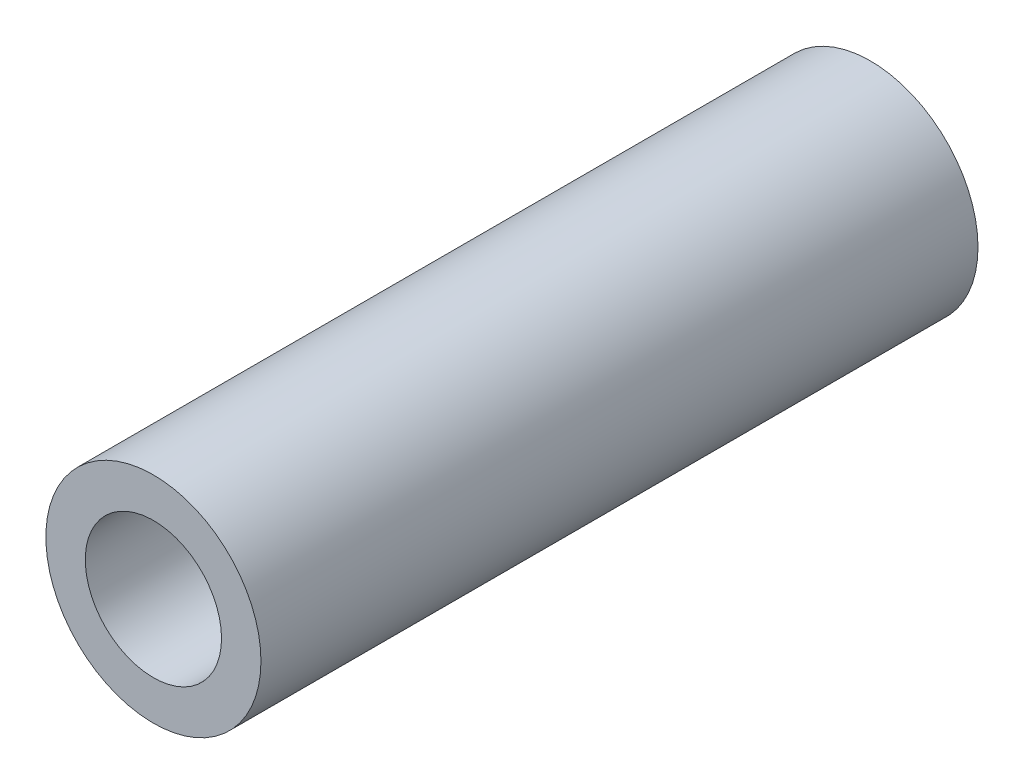
SolidWorks part; units mm, degrees
ref_plane "Front Plane" through (0, 0, 0) normal (0, 0, 1) x (1, 0, 0)
ref_plane "Top Plane" through (0, 0, 0) normal (0, 1, 0) x (1, 0, 0)
ref_plane "Right Plane" through (0, 0, 0) normal (1, 0, 0) x (0, 0, -1)
sketch "Sketch2" plane through (0, 0, 0) normal (0, 0, 1) x (1, 0, 0)
  circle A0 centre (0, 0) radius 7.62
  circle A1 centre (0, 0) radius 4.826
  dimension "D1" = 15.24
  dimension "D2" = 9.652
extrude "Boss-Extrude1" add sketch "Sketch2" along normal blind 50.8
